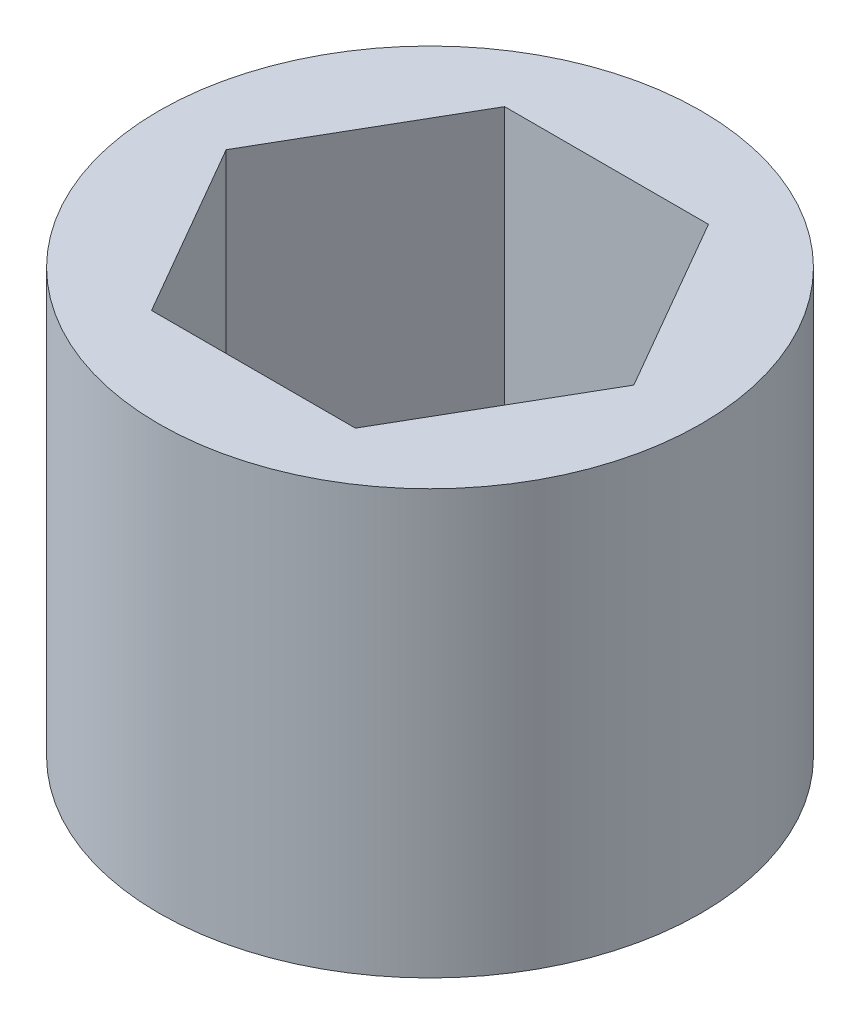
SolidWorks part; units mm, degrees
material "Delrin 2700 NC010, Low Viscosity Acetal Copolymer (SS)"
ref_plane "Front Plane" through (0, 0, 0) normal (0, 0, 1) x (1, 0, 0)
ref_plane "Top Plane" through (0, 0, 0) normal (0, 1, 0) x (1, 0, 0)
ref_plane "Right Plane" through (0, 0, 0) normal (1, 0, 0) x (0, 0, -1)
sketch "Sketch1" plane through (0, 0, 0) normal (0, 1, 0) x (1, 0, 0)
  line L1 (-3.6662, 6.35) -> (-7.3323, 0)
  line L2 (-7.3323, 0) -> (-3.6662, -6.35)
  line L3 (-3.6662, -6.35) -> (3.6662, -6.35)
  line L4 (3.6662, -6.35) -> (7.3323, 0)
  line L5 (7.3323, 0) -> (3.6662, 6.35)
  line L6 (3.6662, 6.35) -> (-3.6662, 6.35)
  circle A0 centre (0, 0) radius 9.7536
  circle A1 centre (0, 0) radius 6.35 construction
  dimension "D1" = 19.5072
  dimension "D2" = 12.7
extrude "Boss-Extrude1" add sketch "Sketch1" along normal blind 15.24
